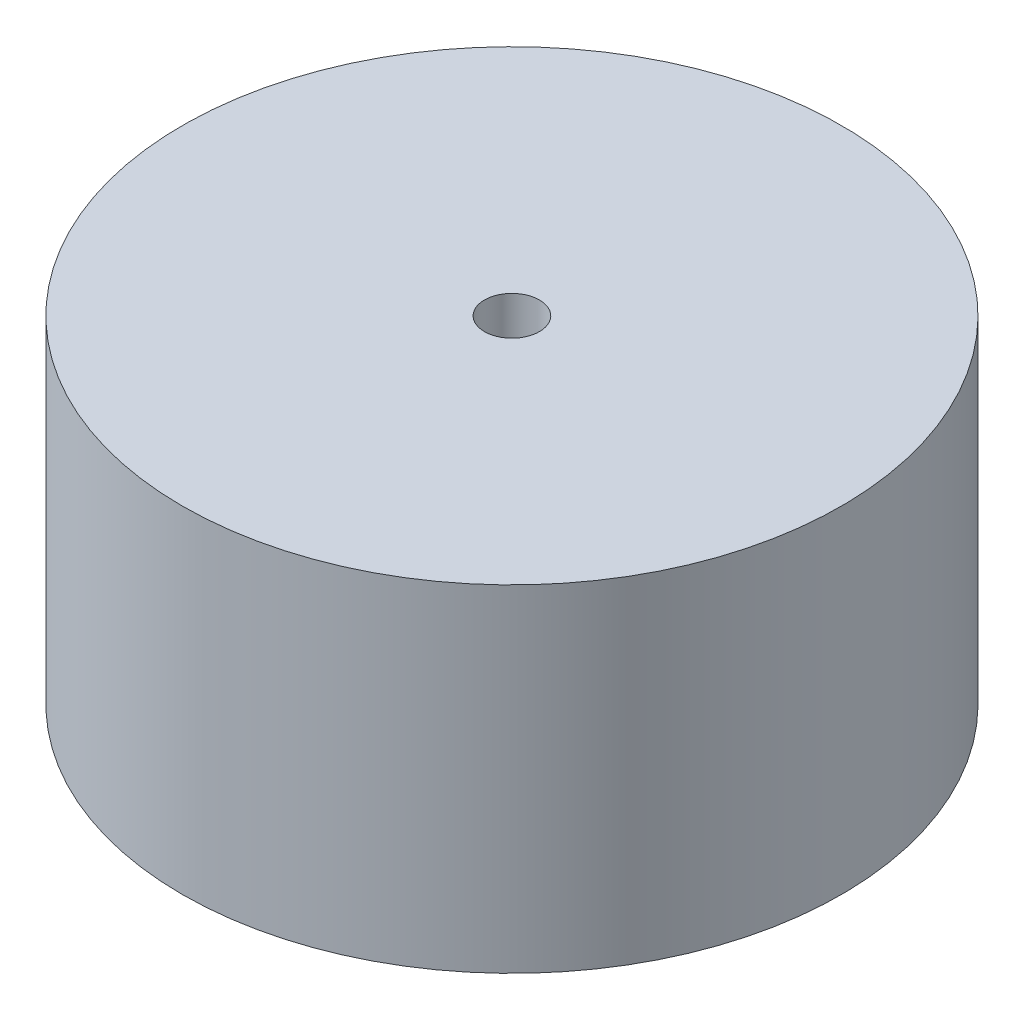
SolidWorks part; units mm, degrees
ref_plane "前视基准面" through (0, 0, 0) normal (0, 0, 1) x (1, 0, 0)
ref_plane "上视基准面" through (0, 0, 0) normal (0, 1, 0) x (1, 0, 0)
ref_plane "右视基准面" through (0, 0, 0) normal (1, 0, 0) x (0, 0, -1)
sketch "草图1" plane through (0, 0, 0) normal (0, 1, 0) x (1, 0, 0)
  circle A0 centre (0, 0) radius 24
  dimension "D1" = 48
extrude "凸台-拉伸2" add sketch "草图1" along normal blind 24.5
sketch "草图2" plane through (0, 24.5, 0) normal (0, 1, 0) x (1, 0, 0)
  circle A0 centre (0, 0) radius 2
  dimension "D1" = 4
extrude "切除-拉伸1" cut sketch "草图2" against normal through all both and the other way through all
